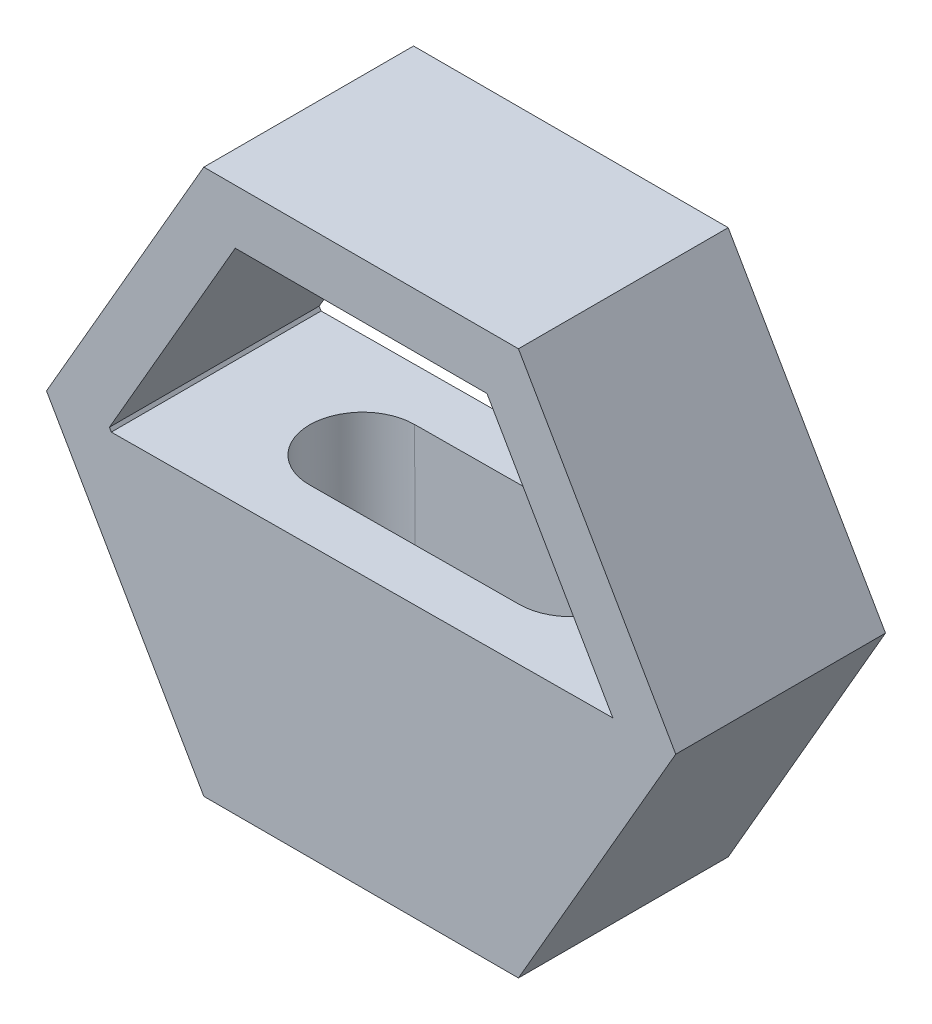
SolidWorks part; units mm, degrees
ref_plane "Front Plane" through (0, 0, 0) normal (0, 0, 1) x (1, 0, 0)
ref_plane "Top Plane" through (0, 0, 0) normal (0, 1, 0) x (1, 0, 0)
ref_plane "Right Plane" through (0, 0, 0) normal (1, 0, 0) x (0, 0, -1)
sketch "Sketch1" plane through (0, 0, 0) normal (0, 0, 1) x (1, 0, 0)
  line L5 (150, 0) -> (75, 129.9038)
  line L6 (75, 129.9038) -> (-75, 129.9038)
  line L7 (-75, 129.9038) -> (-150, 0)
  line L8 (-150, 0) -> (-75, -129.9038)
  line L9 (-75, -129.9038) -> (75, -129.9038)
  line L10 (75, -129.9038) -> (150, 0)
  circle A0 centre (0, 0) radius 129.9038 construction
extrude "Boss-Extrude1" add sketch "Sketch1" against normal blind 100
sketch "Sketch2" plane through (0, 0, 0) normal (0, 0, 1) x (1, 0, 0)
  line L6 (-119.0976, -1.5629) -> (120, 0)
  line L7 (120, 0) -> (60, 103.923)
  line L8 (60, 103.923) -> (-60, 103.923)
  line L9 (-60, 103.923) -> (-120, 0)
  line L10 (-120, 0) -> (-60, -103.923)
  line L11 (-60, -103.923) -> (60, -103.923)
  line L12 (60, -103.923) -> (120, 0)
  circle A0 centre (0, 0) radius 103.923 construction
extrude "Cut-Extrude1" cut sketch "Sketch2" against normal blind 100 contours L9 L10 L6 L7 L8
sketch "Sketch3" plane through (0.0051, -0.7844, 0) normal (-0.0065, 1, 0) x (1, 0.0065, 0)
  line L0 (0.4461, 100) -> (0.4461, 0)
  line L1 (-119.1053, 100) -> (119.9974, 100) construction
  line L2 (-119.1053, 0) -> (119.9974, 0) construction
  line L3 (0.4461, 50) -> (50.4461, 50) construction
  line L4 (0.4461, 75) -> (50.4461, 75)
  line L5 (0.4461, 25) -> (50.4461, 25)
  line L6 (0.4461, 50) -> (-49.5539, 50) construction
  line L7 (0.4461, 25) -> (-49.5539, 25)
  line L8 (0.4461, 75) -> (-49.5539, 75)
  arc A0 (0.4461, 75) -> (0.4461, 25) centre (0.4461, 50) ccw
  arc A1 (50.4461, 25) -> (50.4461, 75) centre (50.4461, 50) ccw
  arc A2 (0.4461, 25) -> (0.4461, 75) centre (0.4461, 50) ccw
  arc A3 (-49.5539, 75) -> (-49.5539, 25) centre (-49.5539, 50) ccw
  point P8 (25.4461, 50)
  point P13 (-24.5539, 50)
extrude "Cut-Extrude2" cut sketch "Sketch3" against normal blind 100 contours L8 A3 L7 A0 | L0 A0 | L0 A2 | A2 L5 A1 L4
